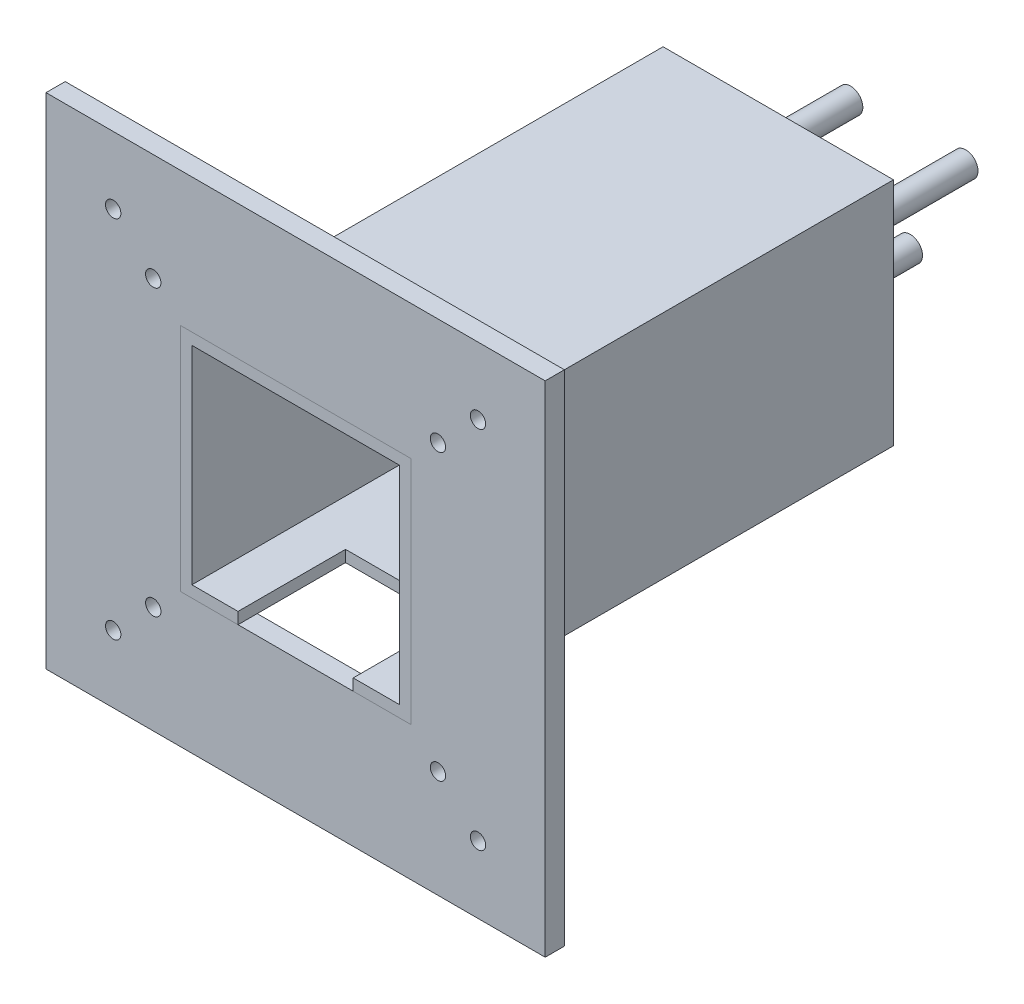
SolidWorks part; units mm, degrees
ref_plane "Front Plane" through (0, 0, 0) normal (0, 0, 1) x (1, 0, 0)
ref_plane "Top Plane" through (0, 0, 0) normal (0, 1, 0) x (1, 0, 0)
ref_plane "Right Plane" through (0, 0, 0) normal (1, 0, 0) x (0, 0, -1)
sketch "Sketch1" plane through (0, 0, 0) normal (0, 0, 1) x (1, 0, 0)
  line L0 (-18.0519, -15.1079) -> (-0.0519, -15.1079)
  line L1 (-39.0112, 23.874) -> (20.9888, 23.874)
  line L2 (-39.0112, 23.874) -> (-39.0112, -36.126)
  line L3 (-39.0112, -36.126) -> (20.9888, -36.126)
  line L4 (20.9888, 23.874) -> (20.9888, -36.126)
  line L5 (-17.9955, 2.8921) -> (-18.0519, -15.1079)
  line L6 (-17.9955, 2.8921) -> (0.0045, 2.8921)
  circle A0 centre (-9.0112, -6.126) radius 9
  circle A1 centre (-17.9955, 2.8921) radius 1.5
  circle A2 centre (-18.0519, -15.1079) radius 1.5
  circle A3 centre (0.0045, 2.8921) radius 1.5
  circle A4 centre (-0.0519, -15.1079) radius 1.5
  arc A5 (0.0045, 2.8921) -> (-0.0519, -15.1079) centre (-2873.2155, 2.8921) cw
  dimension "D3" = 30
  dimension "D5" = 18
  dimension "D1" = 60
  dimension "D2" = 60
  dimension "D4" = 30
  dimension "D6" = 18
  dimension "D7" = 18
  dimension "D8" = 18
  dimension "D9" = 18
  dimension "D10" = 18
extrude "Boss-Extrude1" add sketch "Sketch1" along normal blind 4 contours L4 L1 L2 L3 A3 A5 A4 L0 A2 L5 A1 L6 A0 | A5 A3 L6 A0 A1 L5 A2 L0 A4
sketch "Sketch2" plane through (0, 0, 4) normal (0, 0, 1) x (1, 0, 0)
  circle A0 centre (-9.0112, -6.126) radius 16
  circle A1 centre (-9.0112, -6.126) radius 18
  dimension "D1" = 32
  dimension "D2" = 36
extrude "Boss-Extrude2" add sketch "Sketch2" along normal blind 30
sketch "Sketch4" plane through (0, 0, 0) normal (0, 0, -1) x (-1, 0, 0)
  circle A0 centre (9.0112, -6.126) radius 17.3205
  circle A1 centre (-5.8035, 2.8475) radius 2.7
  circle A2 centre (24.1898, 2.2172) radius 2.7
  circle A3 centre (8.6472, -23.4427) radius 2.7
  circle A4 centre (-5.8035, 2.8475) radius 3.2
  circle A5 centre (24.1898, 2.2172) radius 3.2
  circle A6 centre (8.6472, -23.4427) radius 3.2
  dimension "D1" = 5.4
  dimension "D2" = 5.4
  dimension "D3" = 5.4
  dimension "D4" = 30
  dimension "D5" = 30
  dimension "D6" = 30
extrude "Boss-Extrude6" add sketch "Sketch4" along normal blind 34 contours A0 A4 A1 | A0 A4 A1 | A0 A6 A3 | A0 A6 A3 | A2 | A5
sketch "Sketch5" plane through (0, 0, 4) normal (0, 0, 1) x (1, 0, 0)
  line L1 (-39.0112, 23.874) -> (20.9888, 23.874)
  line L2 (-39.0112, 23.874) -> (-39.0112, -36.126)
  line L3 (-39.0112, -36.126) -> (20.9888, -36.126)
  line L4 (20.9888, 23.874) -> (20.9888, -36.126)
  line L5 (-36.0112, 20.874) -> (17.9888, 20.874)
  line L6 (-36.0112, 20.874) -> (-36.0112, -33.126)
  line L7 (-36.0112, -33.126) -> (17.9888, -33.126)
  line L8 (17.9888, 20.874) -> (17.9888, -33.126)
  point P10 (14.522, -28.0724)
  dimension "D1" = 3
  dimension "D2" = 3
  dimension "D3" = 3
  dimension "D4" = 3
extrude "Boss-Extrude7" add sketch "Sketch5" along normal blind 121.7
sketch "Sketch7" plane through (0, -36.126, 0) normal (0, -1, 0) x (1, 0, 0)
  line L0 (-39.0112, 125.7) -> (20.9888, 125.7) construction
  line L1 (-24.0112, 125.7) -> (5.9888, 125.7)
  line L2 (-24.0112, 125.7) -> (-24.0112, 97.7)
  line L3 (-24.0112, 97.7) -> (5.9888, 97.7)
  line L4 (5.9888, 125.7) -> (5.9888, 97.7)
  line L5 (20.9888, 125.7) -> (20.9888, 0) construction
  line L6 (-39.0112, 125.7) -> (-39.0112, 0) construction
  dimension "D1" = 28
  dimension "D2" = 30
  dimension "D3" = 15
  dimension "D4" = 15
extrude "Cut-Extrude1" cut sketch "Sketch7" against normal blind 30.7
sketch "Sketch8" plane through (0, 0, 125.7) normal (0, 0, 1) x (1, 0, 0)
  line L0 (-39.0112, 23.874) -> (-39.0112, -36.126) construction
  line L1 (-74.0112, 58.874) -> (55.9888, 58.874)
  line L2 (-74.0112, 58.874) -> (-74.0112, -71.126)
  line L3 (-74.0112, -71.126) -> (55.9888, -71.126)
  line L4 (55.9888, 58.874) -> (55.9888, -71.126)
  line L6 (-24.0112, -36.126) -> (5.9888, -36.126) construction
  line L7 (-74.0112, 58.874) -> (-39.0112, 23.874)
  line L8 (-39.0112, 23.874) -> (20.9888, 23.874)
  line L9 (-39.0112, 23.874) -> (-39.0112, -36.126)
  line L10 (-39.0112, -36.126) -> (20.9888, -36.126)
  line L11 (20.9888, 23.874) -> (20.9888, -36.126)
  line L12 (20.9888, 23.874) -> (55.9888, 58.874)
  line L13 (20.9888, -36.126) -> (55.9888, -71.126)
  line L14 (-39.0112, -36.126) -> (-74.0112, -71.126)
  circle A0 centre (-56.5112, 41.374) radius 2
  circle A1 centre (-56.5112, -53.626) radius 2
  circle A2 centre (38.4888, -53.626) radius 2
  circle A3 centre (38.4888, 41.374) radius 2
  circle A4 centre (28.0599, -43.1971) radius 2
  circle A5 centre (-46.0822, -43.1971) radius 2
  circle A6 centre (-46.0822, 30.9451) radius 2
  circle A7 centre (28.0599, 30.9451) radius 2
  line M16 (5.9888, -36.126) -> (20.9888, -36.126)
  line M17 (20.9888, -36.126) -> (20.9888, 23.874)
  line M18 (20.9888, 23.874) -> (-39.0112, 23.874)
  line M19 (-39.0112, 23.874) -> (-39.0112, -36.126)
  line M20 (-39.0112, -36.126) -> (-24.0112, -36.126)
  dimension "D5" = 4
  dimension "D6" = 4
  dimension "D7" = 10
  dimension "D1" = 130
  dimension "D2" = 130
  dimension "D3" = 35
  dimension "D4" = 35
  dimension "D8" = 10
  dimension "D9" = 10
  dimension "D10" = 10
extrude "Boss-Extrude8" add sketch "Sketch8" against normal blind 5 separate body contours A6 L7 A0 L2 L14 A1 A5 M19 | A7 L12 A3 L1 L7 A0 A6 M18 | A7 L12 L13 A4 A2 L4 A3 M17 | A5 L14 A1 L3 L13 A2 A4 L10 M16 M20
